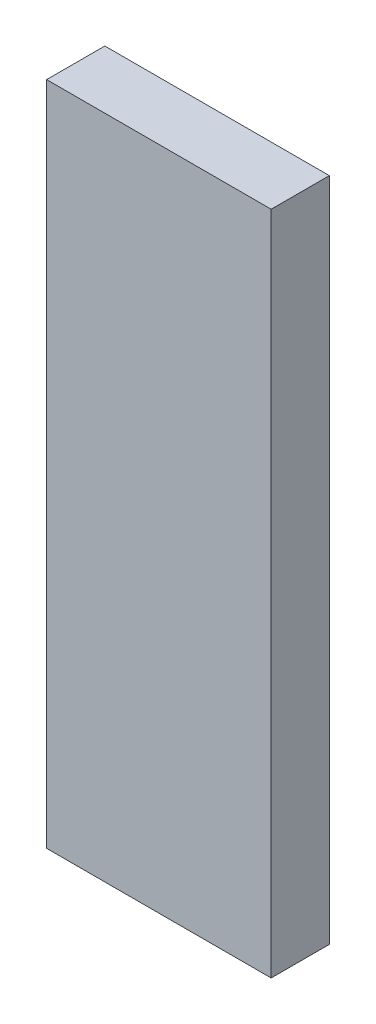
SolidWorks part; units mm, degrees
ref_plane "Front Plane" through (0, 0, 0) normal (0, 0, 1) x (1, 0, 0)
ref_plane "Top Plane" through (0, 0, 0) normal (0, 1, 0) x (1, 0, 0)
ref_plane "Right Plane" through (0, 0, 0) normal (1, 0, 0) x (0, 0, -1)
sketch "Sketch1" plane through (0, 0, 0) normal (0, 1, 0) x (1, 0, 0)
  line L1 (24.5, 6.35) -> (-24.5, 6.35)
  line L2 (24.5, 6.35) -> (24.5, -6.35)
  line L3 (24.5, -6.35) -> (-24.5, -6.35)
  line L4 (-24.5, 6.35) -> (-24.5, -6.35)
  line L5 (24.5, 6.35) -> (-24.5, -6.35) construction
  line L6 (24.5, -6.35) -> (-24.5, 6.35) construction
  point P0 (0, 0)
  dimension "D1" = 12.7
  dimension "D2" = 49
extrude "Boss-Extrude1" add sketch "Sketch1" along normal blind 145.3
